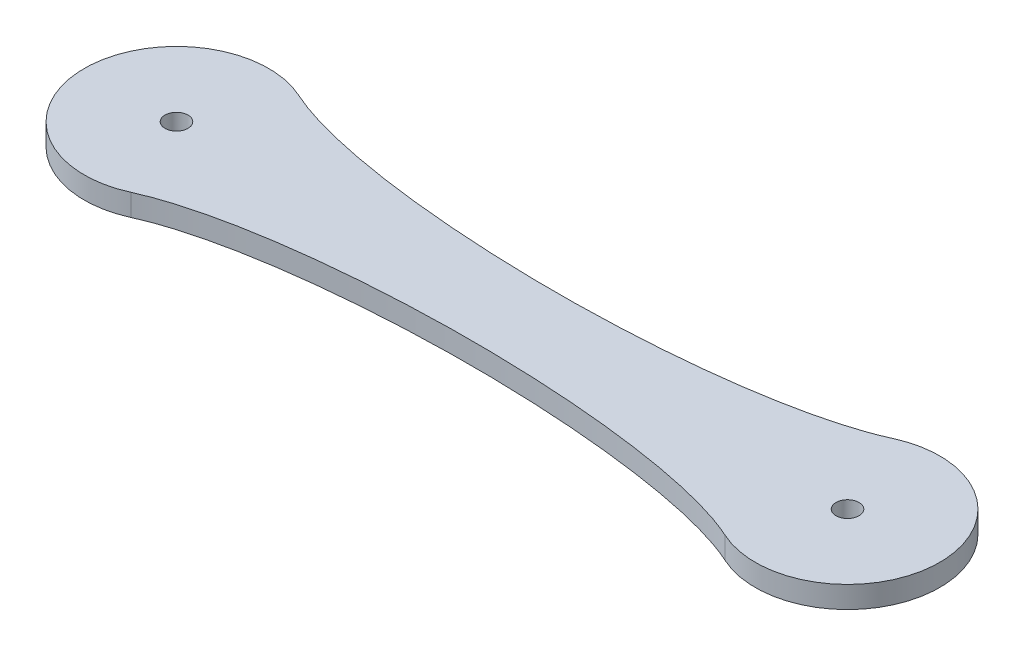
SolidWorks part; units mm, degrees
ref_plane "Front Plane" through (0, 0, 0) normal (0, 0, 1) x (1, 0, 0)
ref_plane "Top Plane" through (0, 0, 0) normal (0, 1, 0) x (1, 0, 0)
ref_plane "Right Plane" through (0, 0, 0) normal (1, 0, 0) x (0, 0, -1)
sketch "Sketch1" plane through (0, 0, 0) normal (0, 1, 0) x (1, 0, 0)
  line L0 (0, 0) -> (80, 0) construction
  line L1 (9.798, 5) -> (70.202, 5) construction
  arc A0 (4.5826, 10) -> (4.5826, -10) centre (0, 0) ccw
  arc A1 (75.4174, -10) -> (75.4174, 10) centre (80, 0) ccw
  arc A2 (4.5826, -10) -> (11, 0) centre (0, 0) ccw construction
  arc A3 (11, 0) -> (9.798, 5) centre (0, 0) ccw construction
  arc A4 (9.798, 5) -> (4.5826, 10) centre (0, 0) ccw construction
  arc A5 (70.202, 5) -> (69, 0) centre (80, 0) ccw construction
  arc A6 (75.4174, 10) -> (70.202, 5) centre (80, 0) ccw construction
  arc A7 (69, 0) -> (75.4174, -10) centre (80, 0) ccw construction
  spline S0 degree 3 poles (4.5826, 10) (11.5631, 6.8011) (40.0993, 3.2164) (68.3601, 6.7659) (75.4174, 10) knots 0 0 0 0 0.499463 1 1 1 1
  spline S1 degree 3 poles (4.5826, -10) (11.5631, -6.8011) (40.0993, -3.2164) (68.3601, -6.7659) (75.4174, -10) knots 0 0 0 0 0.499463 1 1 1 1
  dimension "D1" = 22
  dimension "D2" = 80
  dimension "D3" = 5
  dimension "D4" = 5
extrude "Boss-Extrude1" add sketch "Sketch1" along normal blind 2.6 contours A0 S1 A1 S0
sketch "Sketch3" plane through (0, 2.6, 0) normal (0, 1, 0) x (1, 0, 0)
  arc A0 (4.5826, 10) -> (4.5826, -10) centre (0, 0) ccw construction
  arc A1 (4.5826, 10) -> (4.5826, -10) centre (0, 0) ccw construction
  arc A2 (75.4174, -10) -> (75.4174, 10) centre (80, 0) ccw construction
  arc A3 (75.4174, -10) -> (75.4174, 10) centre (80, 0) ccw construction
  circle A4 centre (0, 0) radius 1.375
  circle A5 centre (80, 0) radius 1.375
  dimension "D1" = 2.75
extrude "Cut-Extrude1" cut sketch "Sketch3" against normal up to next
equation "\"PWThickness\" = 2.6"
equation "\"D1@Boss-Extrude1\"=\"PWThickness\""
